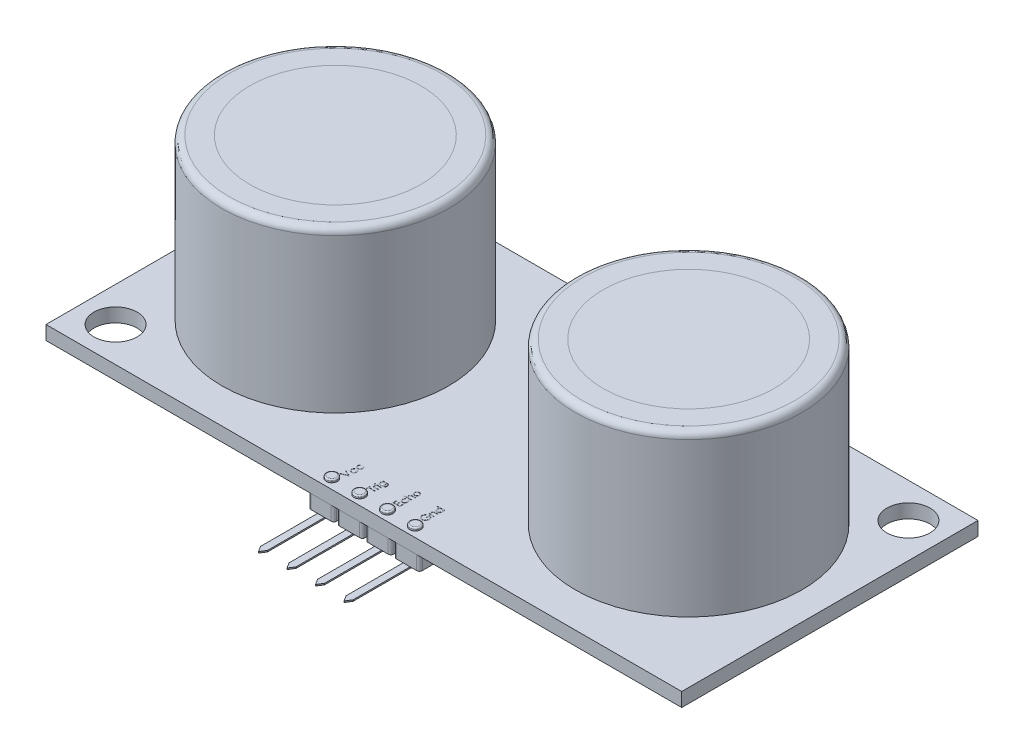
SolidWorks part; units mm, degrees
ref_plane "Front Plane" through (0, 0, 0) normal (0, 0, 1) x (1, 0, 0)
ref_plane "Top Plane" through (0, 0, 0) normal (0, 1, 0) x (1, 0, 0)
ref_plane "Right Plane" through (0, 0, 0) normal (1, 0, 0) x (0, 0, -1)
sketch "Sketch1" plane through (0, 0, 0) normal (0, 1, 0) x (1, 0, 0)
  line L1 (22.85, -10.65) -> (-22.85, -10.65)
  line L2 (22.85, -10.65) -> (22.85, 10.65)
  line L3 (22.85, 10.65) -> (-22.85, 10.65)
  line L4 (-22.85, -10.65) -> (-22.85, 10.65)
  line L5 (22.85, -10.65) -> (-22.85, 10.65) construction
  line L6 (22.85, 10.65) -> (-22.85, -10.65) construction
  circle A0 centre (20.35, 8.15) radius 1.55
  circle A1 centre (-20.35, -8.15) radius 1.55
  point P0 (0, 0)
  dimension "D3" = 3.1
  dimension "D1" = 45.7
  dimension "D2" = 21.3
  dimension "D4" = 2.5
  dimension "D5" = 2.5
  dimension "D6" = 2.5
  dimension "D7" = 2.5
extrude "Boss-Extrude1" add sketch "Sketch1" along normal blind 1
sketch "Sketch2" plane through (0, 1, 0) normal (0, 1, 0) x (1, 0, 0)
  line L0 (0, 0) -> (0, -50000) construction
  circle A0 centre (-12.7, 0) radius 8.15
  circle A1 centre (12.7, 0) radius 8.15
  circle A2 centre (-12.7, 0) radius 6.15
  circle A3 centre (12.7, 0) radius 6.15
  point P4 (20.85, 0)
  point P6 (-20.85, 0)
  dimension "D1" = 16.3
  dimension "D2" = 41.7
  dimension "D3" = 20.85
  dimension "D4" = 2
extrude "Boss-Extrude2" add sketch "Sketch2" along normal blind 11.54 separate body
fillet "Fillet1" radius 0.5 1 edges at (-12.7, 12.54, 8.15)
fillet "Fillet2" radius 0.5 1 edges at (12.7, 12.54, 8.15)
sketch "Sketch3" plane through (0, 1, 0) normal (0, 1, 0) x (1, 0, 0)
  circle A0 centre (-12.7, 0) radius 6
  circle A1 centre (12.7, 0) radius 6
  dimension "D1" = 12
extrude "Boss-Extrude3" add sketch "Sketch3" along normal blind 7 separate body
ref_plane "Plane1" through (12.7, 0, 0) normal (1, 0, 0) x (0, 0, -1)
sketch "Sketch5" plane through (12.7, 0, 0) normal (1, 0, 0) x (0, 0, -1)
  line L0 (0, 8) -> (0, -49992) construction
  line L1 (6, 8) -> (-6, 8) construction
  line L2 (0.75, 8.5) -> (0.75, 8.4)
  line L4 (0.75, 8.5) -> (0, 8.5)
  line L5 (4, 8.915) -> (2, 8)
  line L6 (0.75, 8.4) -> (0.95, 8.4)
  line L7 (0, 8.5) -> (0, 8)
  line L8 (0, 8) -> (2, 8)
  line L9 (0.95, 8.4) -> (4, 8.915)
  point P4 (0, 8)
  dimension "D1" = 4
  dimension "D2" = 0.5
  dimension "D3" = 0.75
  dimension "D4" = 0.1
  dimension "D5" = 2
  dimension "D6" = 15
  dimension "D7" = 0.2
revolve "Revolve1" add sketch "Sketch5" angle 360 about L0
pattern_linear "LPattern2" count 2 spacing 25.4 along (-1, 0, 0) of "Revolve1"
sketch "Sketch6" plane through (0, 12.54, 0) normal (0, 1, 0) x (1, 0, 0)
  circle A0 centre (-12.7, 0) radius 6.15
  circle A1 centre (12.7, 0) radius 6.15
  dimension "D1" = 12.3
extrude "Boss-Extrude4" add sketch "Sketch6" against normal blind 0.2 separate body
sketch "Sketch18" plane through (0, 0, 0) normal (0, -1, 0) x (1, 0, 0)
  line L0 (-22.85, 10.65) -> (22.85, 10.65) construction
  line L1 (-3.8, 10.65) -> (-2.35, 10.65)
  line L2 (-4, 10.45) -> (-4, 8.85)
  line L3 (-3.8, 8.65) -> (-2.35, 8.65)
  line L4 (4, 10.45) -> (4, 8.85)
  line L5 (0, 8.65) -> (0, 10.65) construction
  line L6 (-4, 9.65) -> (4, 9.65) construction
  line L7 (0, 0) -> (0, 50000) construction
  line L8 (-2.15, 10.45) -> (-2.15, 8.85)
  line L9 (0.1, 10.45) -> (0.1, 8.85)
  line L10 (-1.95, 10.45) -> (-1.95, 8.85)
  line L11 (-1.75, 10.65) -> (-0.3, 10.65)
  line L12 (-1.75, 8.65) -> (-0.3, 8.65)
  line L13 (-0.1, 8.85) -> (-0.1, 10.45)
  line L14 (0.3, 10.65) -> (1.75, 10.65)
  line L15 (0.3, 8.65) -> (1.75, 8.65)
  line L16 (1.95, 10.45) -> (1.95, 8.85)
  line L17 (2.15, 10.45) -> (2.15, 8.85)
  line L18 (2.35, 10.65) -> (3.8, 10.65)
  line L19 (2.35, 8.65) -> (3.8, 8.65)
  arc A0 (3.8, 8.65) -> (4, 8.85) centre (3.8, 8.85) ccw
  arc A1 (4, 10.45) -> (3.8, 10.65) centre (3.8, 10.45) ccw
  arc A2 (2.15, 8.85) -> (2.35, 8.65) centre (2.35, 8.85) ccw
  arc A3 (2.15, 10.45) -> (2.35, 10.65) centre (2.35, 10.45) cw
  arc A4 (1.95, 8.85) -> (1.75, 8.65) centre (1.75, 8.85) cw
  arc A5 (1.95, 10.45) -> (1.75, 10.65) centre (1.75, 10.45) ccw
  arc A6 (0.1, 8.85) -> (0.3, 8.65) centre (0.3, 8.85) ccw
  arc A7 (0.1, 10.45) -> (0.3, 10.65) centre (0.3, 10.45) cw
  arc A8 (-0.1, 8.85) -> (-0.3, 8.65) centre (-0.3, 8.85) cw
  arc A9 (-0.1, 10.45) -> (-0.3, 10.65) centre (-0.3, 10.45) ccw
  arc A10 (-1.95, 10.45) -> (-1.75, 10.65) centre (-1.75, 10.45) cw
  arc A11 (-1.95, 8.85) -> (-1.75, 8.65) centre (-1.75, 8.85) ccw
  arc A12 (-2.35, 8.65) -> (-2.15, 8.85) centre (-2.35, 8.85) ccw
  arc A13 (-2.15, 10.45) -> (-2.35, 10.65) centre (-2.35, 10.45) ccw
  arc A14 (-4, 8.85) -> (-3.8, 8.65) centre (-3.8, 8.85) ccw
  arc A15 (-4, 10.45) -> (-3.8, 10.65) centre (-3.8, 10.45) cw
  point P24 (4, 10.65)
  point P27 (2.15, 8.65)
  point P30 (2.15, 10.65)
  point P33 (1.95, 8.65)
  point P38 (0.1, 8.65)
  point P41 (0.1, 10.65)
  point P46 (-0.1, 10.65)
  point P49 (-1.95, 10.65)
  point P52 (-1.95, 8.65)
  point P59 (-4, 8.65)
  point P62 (-4, 10.65)
  point P212 (0, 9.65)
extrude "Boss-Extrude10" add sketch "Sketch18" along normal blind 1 separate body
sketch "Sketch13" plane through (0, 1, 0) normal (0, 1, 0) x (1, 0, 0)
  line L0 (-4, -10.65) -> (-4, -8.7338) construction
  line L1 (-22.85, -10.65) -> (22.85, -10.65) construction
  line L2 (-4, -8.7338) -> (4, -8.7338) construction
  line L3 (4, -8.7338) -> (4, -10.65) construction
  line L4 (4, -10.65) -> (-4, -10.65) construction
  line L5 (0, 0) -> (0, -50000) construction
  circle A0 centre (-3, -9.95) radius 0.4
  circle A1 centre (-1, -9.95) radius 0.4
  circle A2 centre (1, -9.95) radius 0.4
  circle A3 centre (3, -9.95) radius 0.4
  point P9 (-4, -9.6919)
extrude "Boss-Extrude8" add sketch "Sketch13" along normal blind 0.2 separate body
fillet "Fillet3" radius 0.1 1 edges at (-3, 1.2, 10.35)
fillet "Fillet4" radius 0.1 1 edges at (-1, 1.2, 10.35)
fillet "Fillet5" radius 0.1 1 edges at (1, 1.2, 10.35)
fillet "Fillet6" radius 0.1 1 edges at (3, 1.2, 10.35)
sketch "Sketch15" plane through (0, 1, 0) normal (0, 1, 0) x (1, 0, 0)
  line L0 (-22.85, -10.65) -> (22.85, -10.65) construction
  line L1 (3.4865, -7.65) -> (-2.4849, -7.65) construction
  line L2 (3.4865, -7.65) -> (3.4865, -10.65) construction
  line L3 (3.4865, -10.65) -> (-2.4849, -10.65) construction
  line L5 (-2.4849, -7.65) -> (-2.4849, -10.65) construction
  line L6 (3.4865, -7.65) -> (-2.4849, -10.65) construction
  line L7 (3.4865, -10.65) -> (-2.4849, -7.65) construction
  text T0 "Vcc  \r\nTrig   \r\nEcho\r\nGnd " font "Century Gothic" height 0.5
  point P0 (0.5008, -9.15)
  dimension "D1" = 3
extrude "Cut-Extrude5" cut sketch "Sketch15" against normal blind 0.01
sketch "Sketch19" plane through (0, -1, 0) normal (0, -1, 0) x (1, 0, 0)
  line L1 (3.325, 9.15) -> (2.825, 9.15)
  line L2 (3.325, 9.15) -> (3.325, 14.75)
  line L3 (3.075, 15.15) -> (2.825, 15.15)
  line L4 (2.825, 9.15) -> (2.825, 14.75)
  line L5 (3.075, 15.15) -> (3.075, 9.15) construction
  line L6 (3.325, 12.15) -> (2.825, 12.15) construction
  line L7 (1.275, 9.15) -> (0.775, 9.15)
  line L8 (1.275, 9.15) -> (1.275, 14.75)
  line L9 (1.025, 15.15) -> (0.775, 15.15)
  line L10 (0.775, 9.15) -> (0.775, 14.75)
  line L11 (1.025, 15.15) -> (1.025, 9.15) construction
  line L12 (1.275, 12.15) -> (0.775, 12.15) construction
  line L13 (-0.775, 9.15) -> (-1.275, 9.15)
  line L14 (-0.775, 9.15) -> (-0.775, 14.75)
  line L15 (-1.025, 15.15) -> (-1.275, 15.15)
  line L16 (-1.275, 9.15) -> (-1.275, 14.75)
  line L17 (-1.025, 15.15) -> (-1.025, 9.15) construction
  line L18 (-0.775, 12.15) -> (-1.275, 12.15) construction
  line L19 (-2.825, 9.15) -> (-3.325, 9.15)
  line L20 (-2.825, 9.15) -> (-2.825, 14.75)
  line L21 (-3.075, 15.15) -> (-3.325, 15.15)
  line L22 (-3.325, 9.15) -> (-3.325, 14.75)
  line L23 (-3.075, 15.15) -> (-3.075, 9.15) construction
  line L24 (-2.825, 12.15) -> (-3.325, 12.15) construction
  line L26 (-1.75, 8.65) -> (-0.3, 8.65) construction
  line L27 (-3.8, 8.65) -> (-2.35, 8.65) construction
  line L29 (-3.075, 15.15) -> (-2.825, 14.75)
  line L30 (-3.075, 15.15) -> (-3.325, 14.75)
  line L31 (-1.025, 15.15) -> (-0.775, 14.75)
  line L32 (1.025, 15.15) -> (1.275, 14.75)
  line L33 (-1.275, 14.75) -> (-1.025, 15.15)
  line L34 (1.025, 15.15) -> (0.775, 14.75)
  line L35 (3.075, 15.15) -> (3.325, 14.75)
  line L37 (2.825, 14.75) -> (3.075, 15.15)
  point P20 (-1.025, 8.65)
  point P23 (-3.075, 8.65)
  point P300 (-1.025, 12.15)
  point P301 (-3.075, 12.15)
  point P352 (1.025, 12.15)
  point P420 (3.075, 12.15)
  dimension "D2" = 6
  dimension "D3" = 0.5
  dimension "D4" = 0.5
  dimension "D5" = 0.5
  dimension "D6" = 0.5
  dimension "D7" = 0.4
  dimension "D8" = 0.4
  dimension "D9" = 0.4717
extrude "Boss-Extrude11" add sketch "Sketch19" along normal blind 0.1 separate body contours L29 L20 L19 L22 L30 | L31 L14 L13 L16 L33 | L32 L8 L7 L10 L34 | L35 L2 L1 L4 L37
sketch "Sketch21" plane through (0, 1, 0) normal (0, 1, 0) x (1, 0, 0)
  line L0 (22.85, 10.65) -> (-22.85, 10.65) construction
  line L1 (3, 6.65) -> (-3, 6.65)
  line L3 (3, 9.65) -> (-3, 9.65)
  arc A0 (-3, 9.65) -> (-3, 6.65) centre (-3, 8.15) ccw
  arc A1 (3, 6.65) -> (3, 9.65) centre (3, 8.15) ccw
  point P14 (-4.5, 8.15)
  point P16 (4.5, 8.15)
  dimension "D1" = 3
  dimension "D2" = 6
  dimension "D3" = 1
extrude "Boss-Extrude13" add sketch "Sketch21" along normal blind 0.5 separate body
sketch "Sketch22" plane through (0, 1.5, 0) normal (0, 1, 0) x (1, 0, 0)
  line L1 (-2.9874, 7.15) -> (3, 7.15)
  line L3 (-3, 9.15) -> (3, 9.15)
  line L4 (-3, 6.65) -> (3, 6.65) construction
  arc A0 (-3, 9.15) -> (-2.9874, 7.15) centre (-3, 8.15) ccw
  arc A1 (3, 7.15) -> (3, 9.15) centre (3, 8.15) ccw
  arc A2 (-3, 9.65) -> (-3, 6.65) centre (-3, 8.15) ccw construction
  arc A3 (3, 6.65) -> (3, 9.65) centre (3, 8.15) ccw construction
  point P2 (4.5, 8.15)
  point P3 (4, 8.15)
  point P4 (-4.5, 8.15)
  point P5 (-4, 8.1437)
  dimension "D1" = 0.5
  dimension "D3" = 1
  dimension "D2" = 2
  dimension "D4" = 0.5
  dimension "D5" = 0.5
extrude "Boss-Extrude14" add sketch "Sketch22" along normal blind 1.5
fillet "Fillet7" radius 0.1 8 edges at (-4, 3, -8.1437) (0, 3, -9.15) (4, 3, -8.15) (-4.5, 1.5, -8.15) (0, 1.5, -9.65) (4.5, 1.5, -8.15) (0.0063, 3, -7.15) (0, 1.5, -6.65)
ref_plane "Plane2" through (22.85, 0, -10.65) normal (-1, 0, 0) x (0, 0, 1)
sketch "Sketch24" plane through (0, 0, -10.65) normal (0, 0, -1) x (-1, 0, 0)
  line L0 (0, 1) -> (-13.0885, 500.8287)
  line L1 (-22.85, 1) -> (22.85, 1) construction
  line L2 (-13.0885, 500.8287) -> (13.0885, 500.8287)
  line L3 (13.0885, 500.8287) -> (0, 1)
  line L6 (-3, 2.9) -> (-3, 1.5) construction
  dimension "D1" = 3
  dimension "D2" = 88.5
  dimension "D3" = 500
  dimension "D4" = 3
equation "\"D2@Sketch13\"=\"D1@Sketch13\"/2"
equation "\"D9@Sketch18\"=\"D1@Sketch18\"/2"
